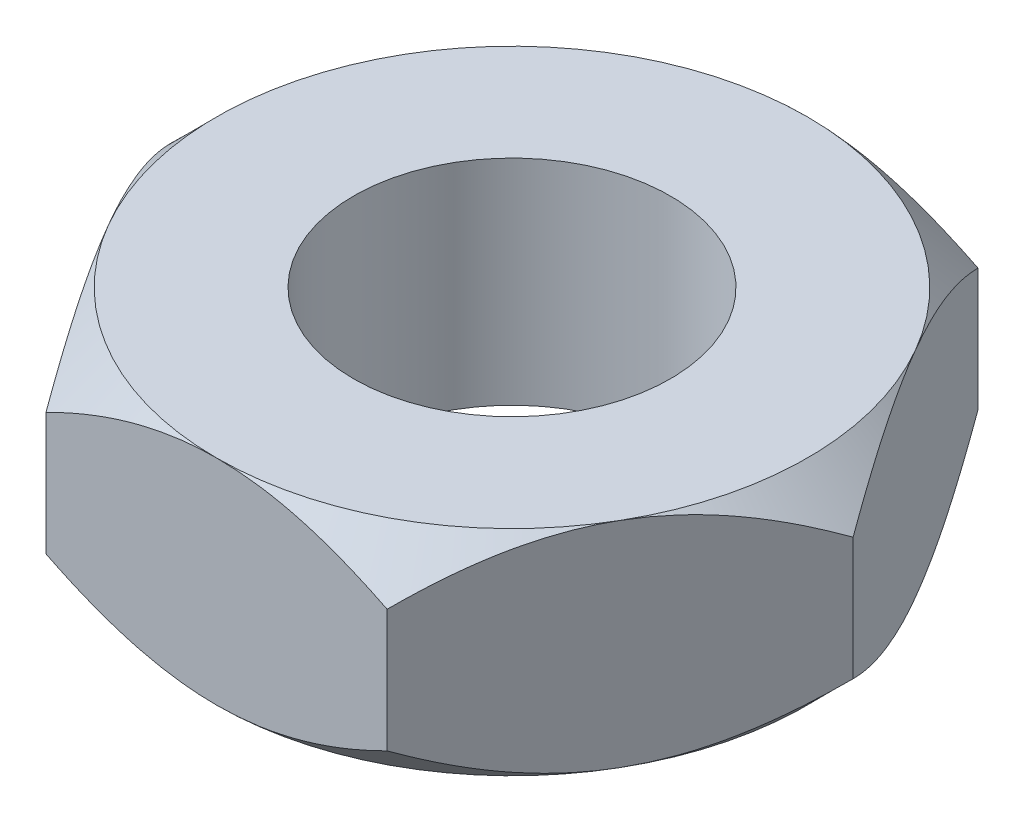
SolidWorks part; units mm, degrees
ref_plane "Front Plane" through (0, 0, 0) normal (0, 0, 1) x (1, 0, 0)
ref_plane "Top Plane" through (0, 0, 0) normal (0, 1, 0) x (1, 0, 0)
ref_plane "Right Plane" through (0, 0, 0) normal (1, 0, 0) x (0, 0, -1)
sketch "Sketch1" plane through (0, 0, 0) normal (0, 1, 0) x (1, 0, 0)
  line L1 (-39.8372, 0) -> (-19.9186, -34.5)
  line L2 (-19.9186, -34.5) -> (19.9186, -34.5)
  line L3 (19.9186, -34.5) -> (39.8372, 0)
  line L4 (39.8372, 0) -> (19.9186, 34.5)
  line L5 (19.9186, 34.5) -> (-19.9186, 34.5)
  line L6 (-19.9186, 34.5) -> (-39.8372, 0)
  circle A0 centre (0, 0) radius 34.5 construction
  circle A1 centre (0, 0) radius 18.5
  dimension "D2" = 37
  dimension "D1" = 69
extrude "Boss-Extrude1" add sketch "Sketch1" along normal mid plane 25
sketch "Sketch2" plane through (0, 12.5, 0) normal (0, 1, 0) x (1, 0, 0)
  line L0 (19.9186, 34.5) -> (-19.9186, 34.5) construction
  circle A0 centre (0, 0) radius 34.5
extrude "Cut-Extrude3" cut sketch "Sketch2" against normal blind 40 draft 45 flip side to cut contours A0
mirror "Mirror1" about plane through (0, 0, 0) normal (0, 1, 0) of "Cut-Extrude3"
